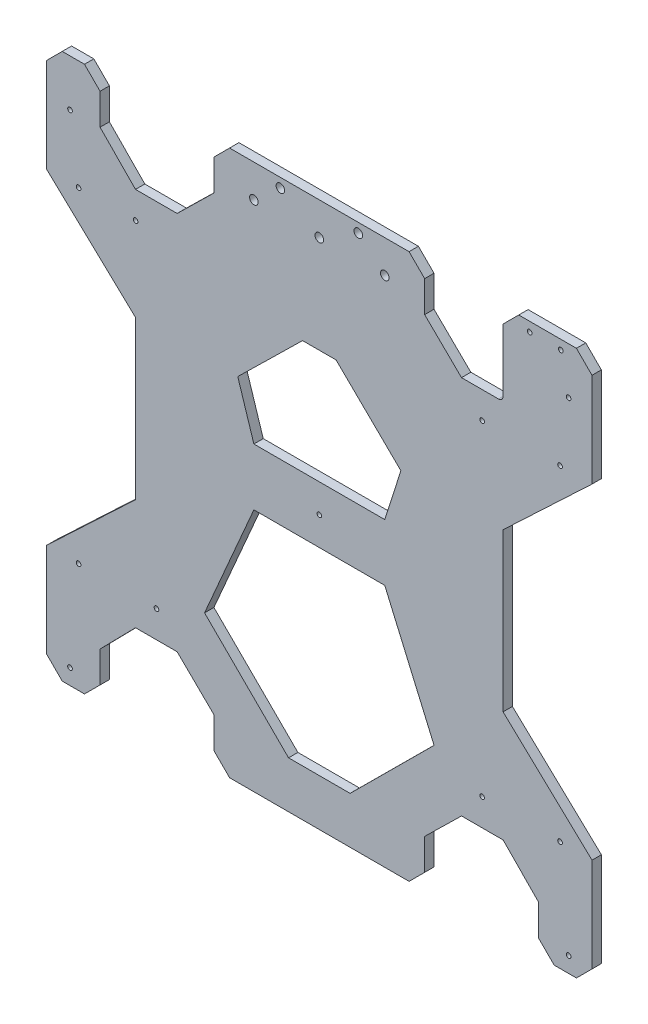
SolidWorks part; units mm, degrees
material "6063-T5"
ref_plane "Piano frontale" through (0, 0, 0) normal (0, 0, 1) x (1, 0, 0)
ref_plane "Piano superiore" through (0, 0, 0) normal (0, 1, 0) x (1, 0, 0)
ref_plane "Piano destro" through (0, 0, 0) normal (1, 0, 0) x (0, 0, -1)
sketch "Schizzo13" plane through (0, 0, 0) normal (0, 0, 1) x (1, 0, 0)
  line L0 (175, 350) -> (175, 0) construction
  line L1 (10, 0) -> (24.282, 0)
  line L2 (0, 279.5) -> (57.0808, 225.6111)
  line L3 (217, 193.2869) -> (227.343, 225.6111)
  line L4 (133, 193.2869) -> (217, 193.2869)
  line L5 (350, 175) -> (0, 175) construction
  line L6 (-60.1887, 10) -> (461.2643, 10) construction
  line L7 (279.5, 279.5) -> (279.5, 175) construction
  line L8 (-12.961, 344) -> (386.8832, 344) construction
  line L9 (-12.961, 329) -> (386.8832, 329) construction
  line L11 (279.5, 70.5) -> (175, 70.5) construction
  line L12 (70.5, 70.5) -> (175, 70.5) construction
  line L14 (57.0808, 279.5) -> (57.0808, 175) construction
  line L15 (57.0808, 279.5) -> (175, 279.5) construction
  line L16 (175, 279.5) -> (329.5, 279.5) construction
  line L17 (329.5, 70.5) -> (329.5, 279.5) construction
  line L18 (20.5, 70.5) -> (329.5, 70.5) construction
  line L19 (20.5, 70.5) -> (20.5, 279.5) construction
  line L20 (175, 279.5) -> (20.5, 279.5) construction
  line L21 (15, -40.9714) -> (15, 408.5301) construction
  line L22 (335, -40.9714) -> (335, 408.5301) construction
  line L23 (-12.961, 320) -> (386.8832, 320) construction
  line L24 (10, 0) -> (0, 10)
  line L25 (340, 0) -> (350, 10)
  line L26 (107.4046, 340) -> (107.4046, 320)
  line L27 (107.4046, 320) -> (83.7454, 296.8073)
  line L28 (57.0808, 279.5) -> (20.5, 279.5) construction
  line L29 (57.0174, 296.8073) -> (34.282, 320)
  line L30 (83.7454, 296.8073) -> (57.0174, 296.8073)
  line L31 (34.282, 320) -> (34.282, 340)
  line L32 (24.282, 350) -> (10, 350)
  line L33 (133, 193.2869) -> (122.657, 225.6111)
  line L34 (57.0808, 279.5) -> (57.0808, 350) construction
  line L35 (164.2491, 266.3832) -> (185.7509, 266.3832)
  line L36 (122.657, 225.6111) -> (164.2491, 266.3832)
  line L37 (57.0808, 225.6111) -> (57.0808, 175)
  line L38 (227.343, 225.6111) -> (185.7509, 266.3832)
  line L39 (292.9192, 225.6111) -> (292.9192, 124.3889)
  line L40 (350, 279.5) -> (292.9192, 225.6111)
  line L44 (292.9826, 299.8073) -> (292.9826, 340)
  line L46 (117.4046, 0) -> (232.5954, 0)
  line L47 (266.2546, 296.8073) -> (289.9826, 296.8073)
  line L48 (242.5954, 320) -> (266.2546, 296.8073)
  line L49 (242.5954, 340) -> (242.5954, 320)
  line L50 (350, 70.5) -> (292.9192, 124.3889)
  line L53 (350, 10) -> (350, 70.5)
  line L55 (315.718, 30) -> (315.718, 10)
  line L56 (292.9826, 53.1927) -> (315.718, 30)
  line L57 (266.2546, 53.1927) -> (292.9826, 53.1927)
  line L58 (242.5954, 30) -> (266.2546, 53.1927)
  line L59 (242.5954, 10) -> (242.5954, 30)
  line L60 (107.4046, 10) -> (107.4046, 30)
  line L61 (107.4046, 30) -> (83.7454, 53.1927)
  line L62 (83.7454, 53.1927) -> (57.0174, 53.1927)
  line L63 (57.0174, 53.1927) -> (34.282, 30)
  line L64 (34.282, 30) -> (34.282, 10)
  line L66 (0, 10) -> (0, 70.5)
  line L69 (0, 70.5) -> (57.0808, 124.3889)
  line L70 (57.0808, 124.3889) -> (57.0808, 175)
  line L71 (0, 279.5) -> (0, 340)
  line L72 (117.4046, 350) -> (232.5954, 350)
  line L73 (302.9826, 350) -> (340, 350)
  line L74 (350, 279.5) -> (350, 340)
  line L75 (325.718, 0) -> (340, 0)
  line L76 (24.282, 0) -> (34.282, 10)
  line L77 (117.4046, 0) -> (107.4046, 10)
  line L78 (232.5954, 0) -> (242.5954, 10)
  line L79 (315.718, 10) -> (325.718, 0)
  line L80 (10, 350) -> (0, 340)
  line L81 (24.282, 350) -> (34.282, 340)
  line L82 (107.4046, 340) -> (117.4046, 350)
  line L83 (232.5954, 350) -> (242.5954, 340)
  line L84 (292.9826, 340) -> (302.9826, 350)
  line L85 (340, 350) -> (350, 340)
  line L86 (133, 156.7131) -> (101.3482, 83.6168)
  line L87 (101.3482, 83.6168) -> (155.2542, 30)
  line L88 (155.2542, 30) -> (194.7458, 30)
  line L89 (133, 156.7131) -> (217, 156.7131)
  line L90 (248.6518, 83.6168) -> (194.7458, 30)
  line L91 (217, 156.7131) -> (248.6518, 83.6168)
  circle A0 centre (15, 320) radius 1.5
  circle A1 centre (20.5, 279.5) radius 1.5
  circle A2 centre (57.0808, 279.5) radius 1.5
  circle A3 centre (175, 175) radius 1.5
  arc A4 (289.9826, 296.8073) -> (292.9826, 299.8073) centre (289.9826, 299.8073) ccw
  circle A5 centre (20.5, 70.5) radius 1.5
  circle A6 centre (200, 344) radius 2.75
  circle A7 centre (150, 344) radius 2.75
  circle A8 centre (175, 329) radius 2.75
  circle A9 centre (217, 329) radius 2.75
  circle A10 centre (133, 329) radius 2.75
  circle A11 centre (70.5, 70.5) radius 1.5
  circle A12 centre (279.5, 70.5) radius 1.5
  circle A13 centre (329.5, 70.5) radius 1.5
  circle A14 centre (335, 10) radius 1.5
  circle A15 centre (15, 10) radius 1.5
  circle A16 centre (279.5, 279.5) radius 1.5
  circle A17 centre (329.5, 279.5) radius 1.5
  circle A18 centre (335, 320) radius 1.5
  circle A19 centre (310, 344) radius 1.5
  circle A20 centre (330, 344) radius 1.5
  point P7 (175, 175)
  point P25 (175, 344)
  point P30 (175, 329)
  point P41 (175, 175)
  point P43 (329.5, 175)
  point P46 (15, 320)
  point P54 (335, 320)
  point P55 (335, 10)
  point P56 (15, 10)
  point P57 (15, 320)
  point P58 (335, 320)
  point P59 (15, 10)
  point P60 (335, 10)
  point P93 (292.9826, 296.8073)
  point P155 (175, 156.7131)
  point P156 (175, 30)
  dimension "D5" = 42
  dimension "D6" = 5.5
  dimension "D7" = 25
  dimension "D8" = 15
  dimension "D10" = 154.5
  dimension "D3" = 104.5
  dimension "D17" = 20
  dimension "D2" = 3
  dimension "D4" = 104.5
  dimension "D11" = 104.5
  dimension "D15" = 310
  dimension "D16" = 320
extrude "Estrusione-Estrusione2" add sketch "Schizzo13" against normal blind 6
sketch "Schizzo14" plane through (0, 0, 0) normal (0, 0, 1) x (1, 0, 0)
  line L0 (350, 350) -> (0, 350)
  line L1 (232.5954, 350) -> (117.4046, 350) construction
  line L2 (0, 350) -> (0, 0)
  line L3 (0, 0) -> (350, 0)
  line L4 (117.4046, 0) -> (232.5954, 0) construction
  line L5 (175, 350) -> (175, 0) construction
  line L6 (350, 350) -> (350, 0)
  circle A0 centre (175, 223.4858) radius 4.4409
  circle A1 centre (175, 78.9698) radius 4.6362
sketch "Schizzo15" plane through (0, 0, 0) normal (0, 0, 1) x (1, 0, 0)
  text T0 "HackerBot" font "Lobster 1.4" height 14
